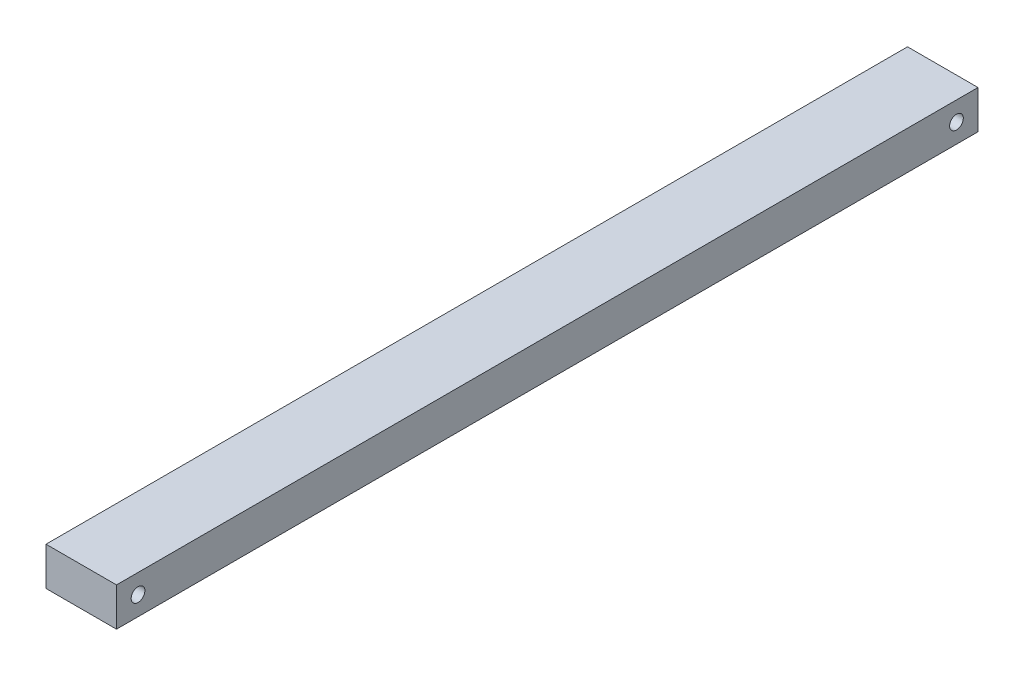
SolidWorks part; units mm, degrees
ref_plane "Front Plane" through (0, 0, 0) normal (0, 0, 1) x (1, 0, 0)
ref_plane "Top Plane" through (0, 0, 0) normal (0, 1, 0) x (1, 0, 0)
ref_plane "Right Plane" through (0, 0, 0) normal (1, 0, 0) x (0, 0, -1)
sketch "Sketch1" plane through (0, 0, 0) normal (0, 1, 0) x (1, 0, 0)
  line L1 (9, 110) -> (-9, 110)
  line L2 (9, 110) -> (9, -110)
  line L3 (9, -110) -> (-9, -110)
  line L4 (-9, 110) -> (-9, -110)
  line L5 (9, 110) -> (-9, -110) construction
  line L6 (9, -110) -> (-9, 110) construction
  point P0 (0, 0)
  dimension "D1" = 18
  dimension "D2" = 220
extrude "Boss-Extrude1" add sketch "Sketch1" along normal blind 9.8
sketch "Sketch3" plane through (-9, 0, 0) normal (-1, 0, 0) x (0, 0, 1)
  line L1 (-110, 0) -> (110, 0) construction
  line L2 (0, -5.39) -> (0, 5.39) construction
  circle A0 centre (-104.5, 4.9) radius 1.75
  circle A1 centre (104.5, 4.9) radius 1.75
  dimension "D2" = 3.5
  dimension "D1" = 4.9
  dimension "D3" = 104.5
extrude "Cut-Extrude1" cut sketch "Sketch3" against normal blind 35
sketch "Sketch4" plane through (-9, 0, 0) normal (-1, 0, 0) x (0, 0, 1)
  circle A0 centre (-104.5, 4.9) radius 2.75
  circle A1 centre (104.5, 4.9) radius 2.75
  dimension "D1" = 5.5
  dimension "D2" = 5.5
extrude "Cut-Extrude2" cut sketch "Sketch4" against normal blind 4
